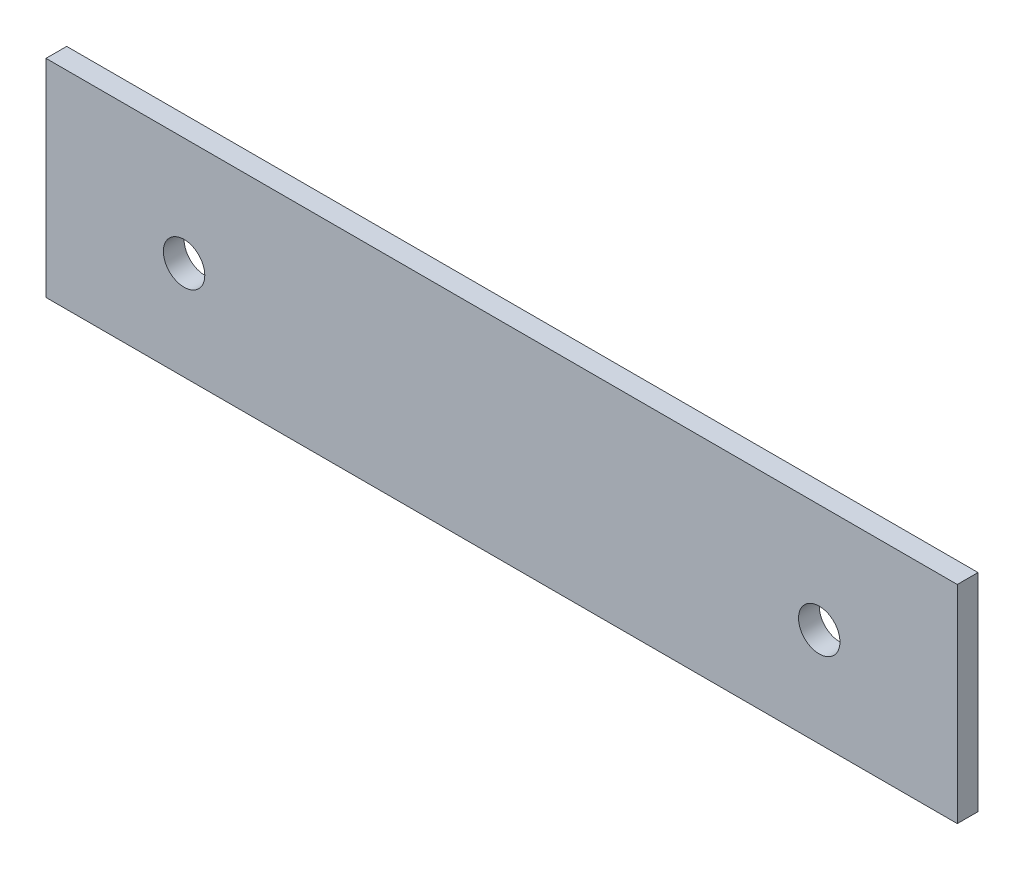
SolidWorks part; units mm, degrees
ref_plane "Plan de face" through (0, 0, 0) normal (0, 0, 1) x (1, 0, 0)
ref_plane "Plan de dessus" through (0, 0, 0) normal (0, 1, 0) x (1, 0, 0)
ref_plane "Plan de droite" through (0, 0, 0) normal (1, 0, 0) x (0, 0, -1)
sketch "Esquisse1" plane through (0, 0, 0) normal (0, 0, 1) x (1, 0, 0)
  line L1 (-26.6554, 19.7623) -> (39.3446, 19.7623)
  line L2 (-26.6554, 19.7623) -> (-26.6554, 4.7623)
  line L3 (-26.6554, 4.7623) -> (39.3446, 4.7623)
  line L4 (39.3446, 19.7623) -> (39.3446, 4.7623)
  circle A0 centre (-16.6554, 11.9049) radius 1.5
  circle A1 centre (29.3446, 11.9049) radius 1.5
  dimension "D3" = 10
  dimension "D1" = 66
  dimension "D2" = 15
  dimension "D4" = 10
extrude "Extrusion1" add sketch "Esquisse1" along normal blind 1.5
